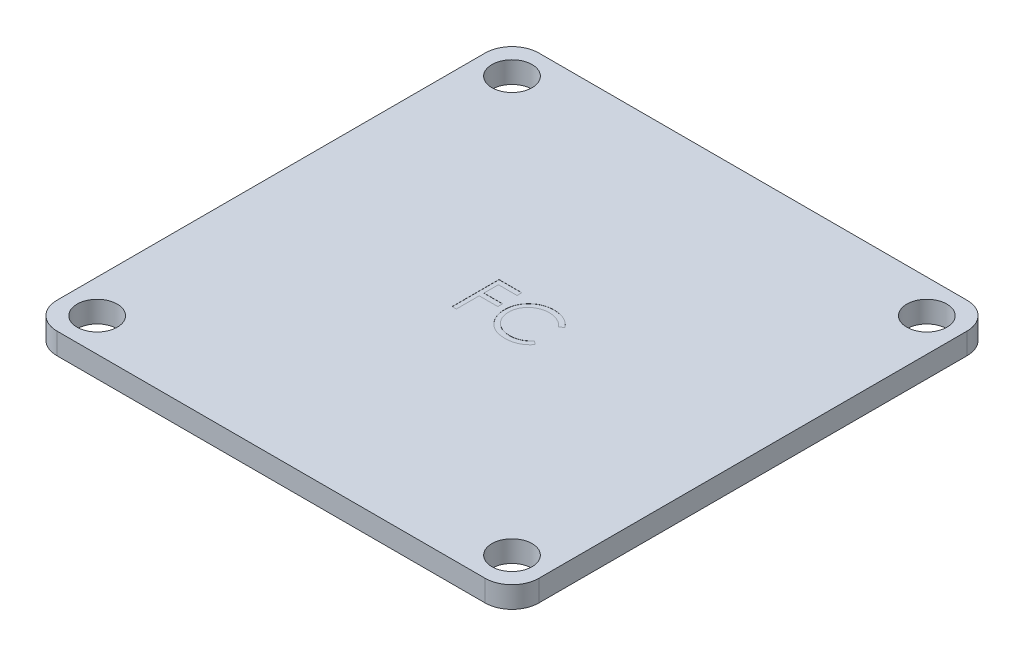
SolidWorks part; units mm, degrees
material "unobtainium"
ref_plane "Front Plane" through (0, 0, 0) normal (0, 0, 1) x (1, 0, 0)
ref_plane "Top Plane" through (0, 0, 0) normal (0, 1, 0) x (1, 0, 0)
ref_plane "Right Plane" through (0, 0, 0) normal (1, 0, 0) x (0, 0, -1)
sketch "Sketch1" plane through (0, 0, 0) normal (0, 1, 0) x (1, 0, 0)
  line L0 (-15.5, 15.5) -> (15.5, 15.5) construction
  line L1 (-18, -18) -> (18, -18)
  line L2 (-18, -18) -> (-18, 18)
  line L3 (-18, 18) -> (18, 18)
  line L4 (18, -18) -> (18, 18)
  line L5 (-18, -18) -> (18, 18) construction
  line L6 (-18, 18) -> (18, -18) construction
  line L7 (-18, 0) -> (18, 0) construction
  circle A0 centre (-15.5, 15.5) radius 1.5
  circle A1 centre (15.5, 15.5) radius 1.5
  circle A2 centre (-15.5, -15.5) radius 1.5
  circle A3 centre (15.5, -15.5) radius 1.5
  point P0 (0, 0)
  dimension "D3" = 3
  dimension "D4" = 3
  dimension "D1" = 36
  dimension "D2" = 36
  dimension "D5" = 31
extrude "Boss-Extrude1" add sketch "Sketch1" along normal blind 1.6
fillet "Fillet1" radius 2 4 edges at (-18, 0.8, -18) (18, 0.8, -18) (-18, 0.8, 18) (18, 0.8, 18)
sketch "Sketch2" plane through (0, 1.6, 0) normal (0, 1, 0) x (1, 0, 0)
  text T0 "FC"
extrude "Cut-Extrude1" cut sketch "Sketch2" against normal blind 0.01
